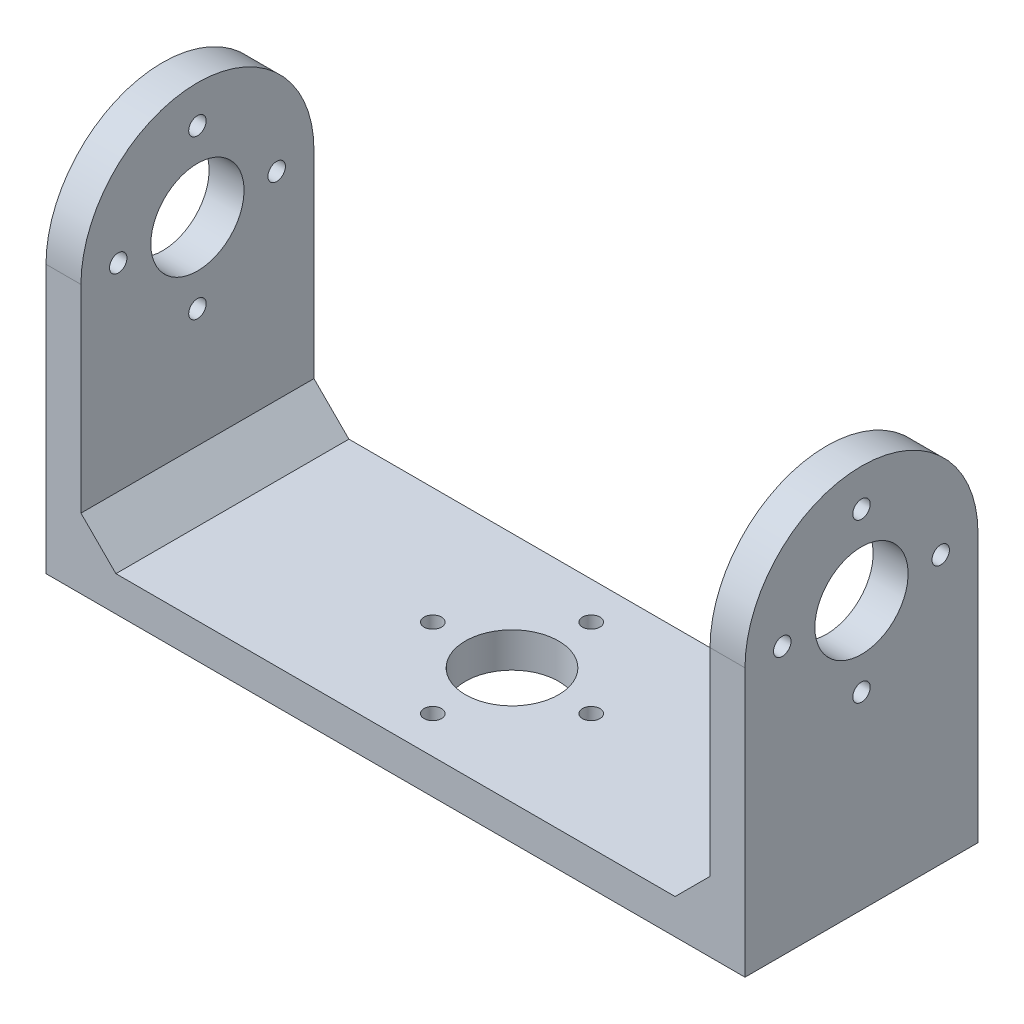
SolidWorks part; units mm, degrees
ref_plane "前视基准面" through (0, 0, 0) normal (0, 0, 1) x (1, 0, 0)
ref_plane "上视基准面" through (0, 0, 0) normal (0, 1, 0) x (1, 0, 0)
ref_plane "右视基准面" through (0, 0, 0) normal (1, 0, 0) x (0, 0, -1)
sketch "草图1" plane through (0, 0, 0) normal (0, 1, 0) x (1, 0, 0)
  line L1 (-30, 10) -> (30, 10)
  line L2 (-30, 10) -> (-30, -10)
  line L3 (-30, -10) -> (30, -10)
  line L4 (30, 10) -> (30, -10)
  dimension "D1" = 60
  dimension "D2" = 20
  dimension "D3" = 30
  dimension "D4" = 10
extrude "凸台-拉伸1" add sketch "草图1" along normal blind 3
sketch "草图2" plane through (30, 0, 0) normal (1, 0, 0) x (0, 0, -1)
  line L0 (-10, 3) -> (-10, 23)
  line L1 (-10, 3) -> (10, 3)
  line L2 (10, 3) -> (10, 23)
  arc A0 (-10, 23) -> (10, 23) centre (0, 23) cw
  dimension "D1" = 20
extrude "凸台-拉伸2" add sketch "草图2" against normal blind 3
sketch "草图3" plane through (-30, 0, 0) normal (-1, 0, 0) x (0, 0, 1)
  line L0 (-10, 3) -> (10, 3)
  line L1 (10, 3) -> (10, 23)
  line L2 (-10, 3) -> (-10, 23)
  arc A0 (-10, 23) -> (10, 23) centre (0, 23) cw
  dimension "D1" = 20
extrude "凸台-拉伸3" add sketch "草图3" against normal blind 3
sketch "草图4" plane through (-30, 0, 0) normal (-1, 0, 0) x (0, 0, 1)
  circle A0 centre (0, 23) radius 4
  circle A1 centre (0, 29.8) radius 0.75
  circle A2 centre (6.8, 23) radius 0.75
  circle A3 centre (0, 16.2) radius 0.75
  circle A4 centre (-6.8, 23) radius 0.75
  point P14 (0, 23)
  dimension "D1" = 8
  dimension "D2" = 1.5
  dimension "D3" = 6.8
  dimension "D4" = 4
extrude "切除-拉伸1" cut sketch "草图4" against normal through all
sketch "草图5" plane through (0, 3, 0) normal (0, 1, 0) x (1, 0, 0)
  circle A0 centre (0, 0) radius 4
  circle A1 centre (0, 6.8) radius 0.75
  circle A2 centre (6.8, 0) radius 0.75
  circle A3 centre (0, -6.8) radius 0.75
  circle A4 centre (-6.8, 0) radius 0.75
  point P14 (0, 0)
  dimension "D1" = 6.8
  dimension "D2" = 1.5
  dimension "D3" = 8
  dimension "D4" = 4
extrude "切除-拉伸2" cut sketch "草图5" against normal blind 3
chamfer "倒角1" distance 3 angle 45 2 edges at (-27, 3, 0)
